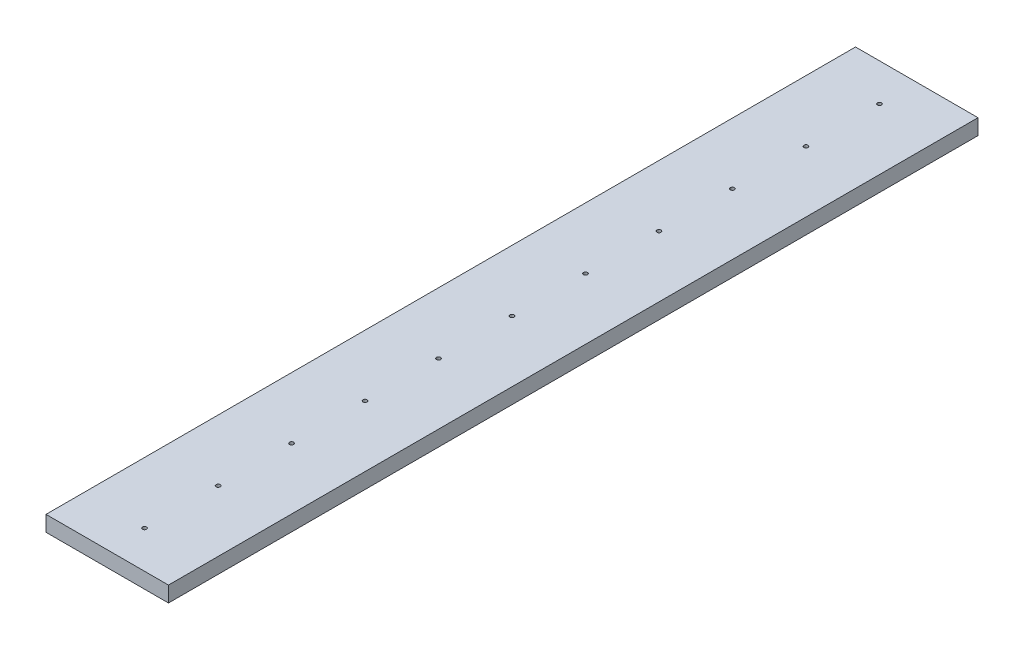
SolidWorks part; units mm, degrees
ref_plane "Front Plane" through (0, 0, 0) normal (0, 0, 1) x (1, 0, 0)
ref_plane "Top Plane" through (0, 0, 0) normal (0, 1, 0) x (1, 0, 0)
ref_plane "Right Plane" through (0, 0, 0) normal (1, 0, 0) x (0, 0, -1)
sketch "Sketch2" plane through (0, 0, 0) normal (0, 1, 0) x (1, 0, 0)
  line L1 (50, 330.5) -> (-50, 330.5)
  line L2 (50, 330.5) -> (50, -330.5)
  line L3 (50, -330.5) -> (-50, -330.5)
  line L4 (-50, 330.5) -> (-50, -330.5)
  line L5 (50, 330.5) -> (-50, -330.5) construction
  line L6 (50, -330.5) -> (-50, 330.5) construction
  point P0 (0, 0)
  dimension "D1" = 100
  dimension "D2" = 661
extrude "Boss-Extrude1" add sketch "Sketch2" along normal blind 12.7
sketch "Sketch3" plane through (0, 12.7, 0) normal (0, 1, 0) x (1, 0, 0)
  line L0 (-50, -330.5) -> (50, -330.5) construction
  point P0 (0, -300)
  point P5 (0, -240)
  point P6 (0, -180)
  point P7 (0, -120)
  point P8 (0, -60)
  point P9 (0, 0)
  point P10 (0, 60)
  point P11 (0, 120)
  point P12 (0, 180)
  point P13 (0, 240)
  point P14 (0, 300)
  point P15 (0, -300)
  point P17 (0, -240)
  point P19 (0, -180)
  point P21 (0, -120)
  point P23 (0, -60)
  point P25 (0, 60)
  point P27 (0, 120)
  point P29 (0, 180)
  point P31 (0, 240)
  point P33 (0, 300)
  dimension "D1" = 30.5
  dimension "D2" = 11
hole_wizard "M4x0.7 Tapped Hole1" positions "Sketch3" profile "Sketch4" tap size "M4x0.7" standard "ANSI Metric"
sketch "Sketch4" plane through (0, 12.7, 300) normal (1, 0, 0) x (0, 0, 1)
  line L0 (0, 0) -> (0, 11.0914)
  line L1 (0, 11.0914) -> (1.65, 10.1)
  line L2 (1.65, 10.1) -> (1.65, 0)
  line L5 (1.65, 0) -> (0, 0)
  line L10 (0, 11.0914) -> (-1.65, 10.1) construction
  line L11 (0, -6.35) -> (0, 107.95) construction
  dimension "Tap Drill Dia." = 3.3
  dimension "Tap Drill Depth" = 10.1
  dimension "Drill Angle" = 118
cosmetic thread "Hole Thread1" parameters "D1"=8, "D2"=4
cosmetic thread "Hole Thread2" parameters "D1"=8, "D2"=4
cosmetic thread "Hole Thread3" parameters "D1"=8, "D2"=4
cosmetic thread "Hole Thread4" parameters "D1"=8, "D2"=4
cosmetic thread "Hole Thread5" parameters "D1"=8, "D2"=4
cosmetic thread "Hole Thread6" parameters "D1"=8, "D2"=4
cosmetic thread "Hole Thread7" parameters "D1"=8, "D2"=4
cosmetic thread "Hole Thread8" parameters "D1"=8, "D2"=4
cosmetic thread "Hole Thread9" parameters "D1"=8, "D2"=4
cosmetic thread "Hole Thread10" parameters "D1"=8, "D2"=4
cosmetic thread "Hole Thread11" parameters "D1"=8, "D2"=4
cosmetic thread "Hole Thread12" parameters "D1"=8, "D2"=4
cosmetic thread "Hole Thread13" parameters "D1"=8, "D2"=4
cosmetic thread "Hole Thread14" parameters "D1"=8, "D2"=4
cosmetic thread "Hole Thread15" parameters "D1"=8, "D2"=4
cosmetic thread "Hole Thread16" parameters "D1"=8, "D2"=4
cosmetic thread "Hole Thread17" parameters "D1"=8, "D2"=4
cosmetic thread "Hole Thread18" parameters "D1"=8, "D2"=4
cosmetic thread "Hole Thread19" parameters "D1"=8, "D2"=4
cosmetic thread "Hole Thread20" parameters "D1"=8, "D2"=4
cosmetic thread "Hole Thread21" parameters "D1"=8, "D2"=4
